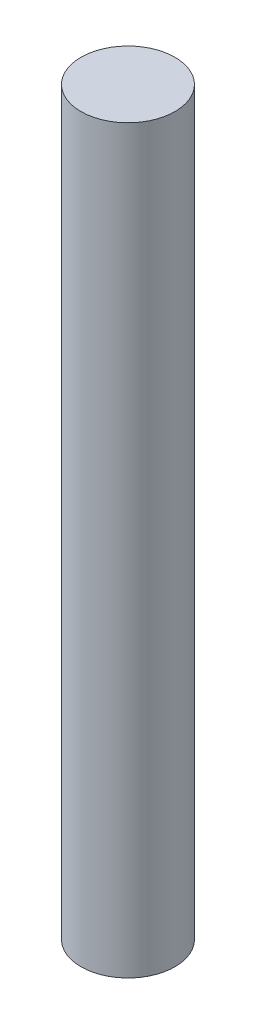
SolidWorks part; units mm, degrees
ref_plane "Front Plane" through (0, 0, 0) normal (0, 0, 1) x (1, 0, 0)
ref_plane "Top Plane" through (0, 0, 0) normal (0, 1, 0) x (1, 0, 0)
ref_plane "Right Plane" through (0, 0, 0) normal (1, 0, 0) x (0, 0, -1)
sketch "Sketch2" plane through (0, 0, 0) normal (0, 1, 0) x (1, 0, 0)
  circle A0 centre (0, 0) radius 3.175
  dimension "D1" = 6.35
extrude "Boss-Extrude1" add sketch "Sketch2" along normal blind 50 contours A0
